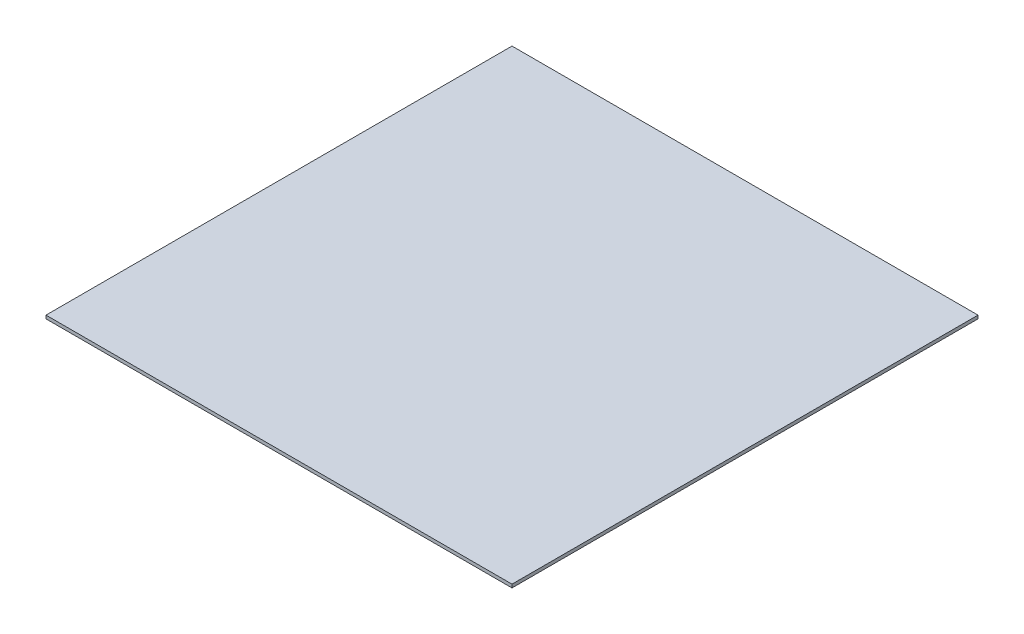
SolidWorks part; units mm, degrees
ref_plane "Front Plane" through (0, 0, 0) normal (0, 0, 1) x (1, 0, 0)
ref_plane "Top Plane" through (0, 0, 0) normal (0, 1, 0) x (1, 0, 0)
ref_plane "Right Plane" through (0, 0, 0) normal (1, 0, 0) x (0, 0, -1)
sketch "Sketch1" plane through (0, 0, 0) normal (0, 1, 0) x (1, 0, 0)
  line L1 (0, 0) -> (450, 0)
  line L2 (0, 0) -> (0, 450)
  line L3 (0, 450) -> (450, 450)
  line L4 (450, 0) -> (450, 450)
  dimension "D1" = 450
  dimension "D2" = 450
extrude "Boss-Extrude1" add sketch "Sketch1" along normal blind 3.175
